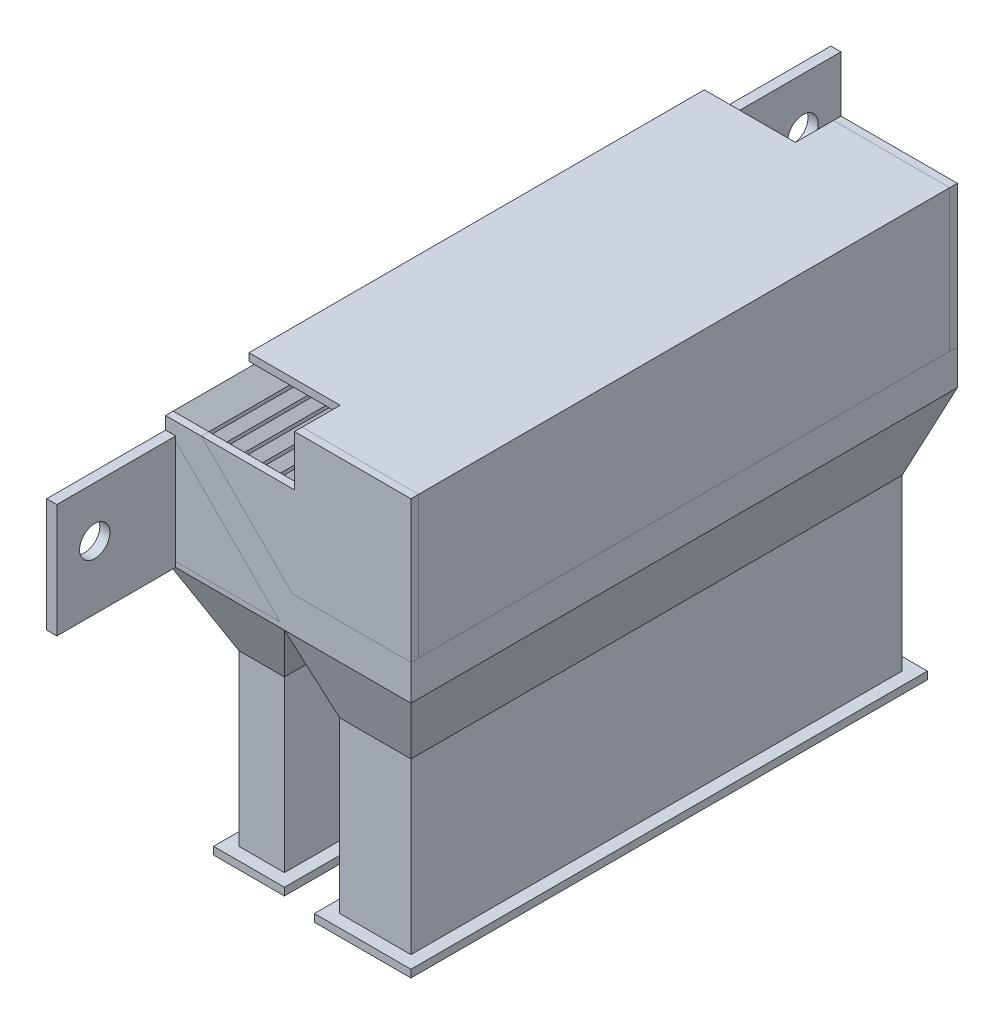
SolidWorks part; units mm, degrees
ref_plane "前视基准面" through (0, 0, 0) normal (0, 0, 1) x (1, 0, 0)
ref_plane "上视基准面" through (0, 0, 0) normal (0, 1, 0) x (1, 0, 0)
ref_plane "右视基准面" through (0, 0, 0) normal (1, 0, 0) x (0, 0, -1)
sketch "草图1" plane through (0, 0, 0) normal (0, 0, 1) x (1, 0, 0)
  line L0 (0, 0) -> (0, 50)
  line L1 (0, 50) -> (50, 0)
  line L3 (0, 0) -> (50, 0)
extrude "拉伸1" add sketch "草图1" along normal blind 216
shell "抽壳1" thickness 2
sketch "草图2" plane through (0, 0, 0) normal (1, 0, 0) x (0, 0, -1)
  line L0 (-216, 25) -> (0, 25) construction
  line L1 (-216, 0) -> (-216, 50) construction
  line L2 (0, 0) -> (0, 50) construction
  line L3 (-108, 50) -> (-108, 0) construction
  line L4 (-216, 50) -> (0, 50) construction
  line L5 (-216, 0) -> (0, 0) construction
  line L7 (-263, 0) -> (47, 0)
  line L8 (-263, 0) -> (-263, 45)
  line L10 (47, 0) -> (47, 45)
  line L15 (-263, 45) -> (47, 45)
  point P12 (-108, 25)
extrude "拉伸3" add sketch "草图2" along normal blind 4
sketch "草图4" plane through (25, 25, 0) normal (0.7071, 0.7071, 0) x (0, 0, -1)
  line L0 (-216, -35.3553) -> (0, -35.3553) construction
  line L1 (-216, 35.3553) -> (-213, 35.3553)
  line L2 (-216, 35.3553) -> (-216, -35.3553)
  line L3 (-216, -35.3553) -> (-213, -35.3553)
  line L4 (-213, 35.3553) -> (-213, -35.3553)
  line L6 (0, 35.3553) -> (-3, 35.3553)
  line L7 (0, 35.3553) -> (0, -35.3553)
  line L8 (0, -35.3553) -> (-3, -35.3553)
  line L9 (-3, 35.3553) -> (-3, -35.3553)
extrude "拉伸4" add sketch "草图4" along normal blind 10
sketch "草图6" plane through (25, 25, 0) normal (0.7071, 0.7071, 0) x (0, 0, -1)
  line L0 (-213, -35.3553) -> (-213, 35.3553) construction
  line L1 (-213, 25.3553) -> (-3, 25.3553)
  line L2 (-213, 25.3553) -> (-213, 24.3553)
  line L3 (-213, 24.3553) -> (-3, 24.3553)
  line L4 (-3, 25.3553) -> (-3, 24.3553)
  line L5 (-3, 35.3553) -> (-3, -35.3553) construction
  line L6 (-213, 35.3553) -> (-3, 35.3553) construction
  line L7 (-3, 20.3553) -> (-3, 19.3553)
  line L8 (-213, 20.3553) -> (-3, 20.3553)
  line L9 (-213, 19.3553) -> (-3, 19.3553)
  line L10 (-213, 20.3553) -> (-213, 19.3553)
  line L11 (-3, 15.3553) -> (-3, 14.3553)
  line L12 (-213, 15.3553) -> (-3, 15.3553)
  line L13 (-213, 14.3553) -> (-3, 14.3553)
  line L14 (-213, 15.3553) -> (-213, 14.3553)
  line L15 (-3, 10.3553) -> (-3, 9.3553)
  line L16 (-213, 10.3553) -> (-3, 10.3553)
  line L17 (-213, 9.3553) -> (-3, 9.3553)
  line L18 (-213, 10.3553) -> (-213, 9.3553)
  line L19 (-3, 5.3553) -> (-3, 4.3553)
  line L20 (-213, 5.3553) -> (-3, 5.3553)
  line L21 (-213, 4.3553) -> (-3, 4.3553)
  line L22 (-213, 5.3553) -> (-213, 4.3553)
  line L23 (-3, 0.3553) -> (-3, -0.6447)
  line L24 (-213, 0.3553) -> (-3, 0.3553)
  line L25 (-213, -0.6447) -> (-3, -0.6447)
  line L26 (-213, 0.3553) -> (-213, -0.6447)
  line L27 (-3, -4.6447) -> (-3, -5.6447)
  line L28 (-213, -4.6447) -> (-3, -4.6447)
  line L29 (-213, -5.6447) -> (-3, -5.6447)
  line L30 (-213, -4.6447) -> (-213, -5.6447)
  line L31 (-3, -9.6447) -> (-3, -10.6447)
  line L32 (-213, -9.6447) -> (-3, -9.6447)
  line L33 (-213, -10.6447) -> (-3, -10.6447)
  line L34 (-213, -9.6447) -> (-213, -10.6447)
  line L35 (-3, -14.6447) -> (-3, -15.6447)
  line L36 (-213, -14.6447) -> (-3, -14.6447)
  line L37 (-213, -15.6447) -> (-3, -15.6447)
  line L38 (-213, -14.6447) -> (-213, -15.6447)
  line L39 (-3, -19.6447) -> (-3, -20.6447)
  line L40 (-213, -19.6447) -> (-3, -19.6447)
  line L41 (-213, -20.6447) -> (-3, -20.6447)
  line L42 (-213, -19.6447) -> (-213, -20.6447)
  line L43 (-3, -24.6447) -> (-3, -25.6447)
  line L44 (-213, -24.6447) -> (-3, -24.6447)
  line L45 (-213, -25.6447) -> (-3, -25.6447)
  line L46 (-213, -24.6447) -> (-213, -25.6447)
  line L47 (-3, -29.6447) -> (-3, -30.6447)
  line L48 (-213, -29.6447) -> (-3, -29.6447)
  line L49 (-213, -30.6447) -> (-3, -30.6447)
  line L50 (-213, -29.6447) -> (-213, -30.6447)
  dimension "D1" = 10
  dimension "D2" = 1
extrude "拉伸5" cut sketch "草图6" against normal blind 3
sketch "草图7" plane through (0, 0, 0) normal (0, -1, 0) x (1, 0, 0)
  line L0 (50, 213) -> (50, 3) construction
  line L3 (44, 213) -> (44, 3)
  line L6 (0, 213) -> (4, 213) construction
  line L7 (44, 213) -> (4, 213)
  line L8 (4, 213) -> (4, 3)
  line L9 (4, 3) -> (44, 3)
  dimension "D1" = 6
extrude "拉伸8" cut sketch "草图7" against normal blind 3
sketch "草图8" plane through (0, 0, 0) normal (0, -1, 0) x (1, 0, 0)
  line L0 (47, 216) -> (47, 0)
  line L5 (1, 0) -> (47, 0)
  line L6 (1, 216) -> (1, 0)
  line L7 (1, 216) -> (47, 216)
extrude "拉伸9" add sketch "草图8" along normal blind 30 draft 25 separate body
sketch "草图9" plane through (0, 0, 0) normal (0, -1, 0) x (1, 0, 0)
  line L4 (47, 216) -> (97, 216)
  line L5 (47, 216) -> (47, 0)
  line L6 (47, 0) -> (97, 0)
  line L7 (97, 216) -> (97, 0)
shell "抽壳2" thickness 3
extrude "拉伸12" add sketch "草图9" along normal blind 30 draft 20 separate body
shell "抽壳3" thickness 3
sketch "草图10" plane through (4, 0, 0) normal (1, 0, 0) x (0, 0, -1)
  line L0 (-263, 0) -> (-216, 0) construction
  line L4 (-263, 45) -> (-263, 0) construction
  line L7 (47, 0) -> (47, 45) construction
  line L8 (0, 0) -> (47, 0) construction
  circle A0 centre (-248, 25) radius 6
  circle A1 centre (32, 25) radius 6
  dimension "D1" = 25
  dimension "D2" = 15
  dimension "D3" = 15
  dimension "D4" = 25
extrude "拉伸13" cut sketch "草图10" against normal blind 30
sketch "草图11" plane through (0, 0, 0) normal (0, 1, 0) x (1, 0, 0)
  line L1 (94, -213) -> (50, -213)
  line L2 (97, 0) -> (50, 0)
  line L3 (97, 0) -> (97, -216)
  line L4 (97, -216) -> (50, -216)
  line L6 (50, -3) -> (50, -213) construction
  line L7 (50, 0) -> (50, -3)
  line L8 (94, -3) -> (50, -3)
  line L9 (94, -3) -> (94, -213)
  line L10 (97, -216) -> (47, -216) construction
  line L11 (50, -213) -> (50, -216)
  line L12 (97, 0) -> (47, 0) construction
  line L18 (47, 0) -> (47, -216) construction
  dimension "D1" = 3
extrude "拉伸15" add sketch "草图11" along normal blind 14
sketch "草图12" plane through (0, 0, -47) normal (0, 0, -1) x (-1, 0, 0)
  line L0 (0, 0) -> (0, 50) construction
  line L1 (0, 0) -> (0, 45) construction
  line L3 (0, 50) -> (-25.0972, 50)
  line L4 (0, 50) -> (0, 57.7185)
  line L5 (0, 57.7185) -> (-25.0972, 57.7185)
  line L6 (-25.0972, 50) -> (-25.0972, 57.7185)
extrude "拉伸16" cut sketch "草图12" against normal blind 300
sketch "草图13" plane through (0, -30, 0) normal (0, -1, 0) x (1, 0, 0)
  line L0 (57.9191, 10.9191) -> (86.0809, 10.9191) construction
  line L1 (57.9191, 205.0809) -> (86.0809, 205.0809)
  line L2 (57.9191, 205.0809) -> (57.9191, 10.9191)
  line L3 (57.9191, 10.9191) -> (86.0809, 10.9191)
  line L4 (86.0809, 205.0809) -> (86.0809, 10.9191)
  line L5 (86.0809, 10.9191) -> (86.0809, 205.0809) construction
  line L6 (60.9191, 202.0809) -> (83.0809, 202.0809)
  line L7 (83.0809, 202.0809) -> (83.0809, 13.9191)
  line L8 (60.9191, 13.9191) -> (83.0809, 13.9191)
  line L9 (60.9191, 202.0809) -> (60.9191, 13.9191)
  dimension "D1" = 3
extrude "拉伸17" add sketch "草图13" along normal blind 70 separate body
sketch "草图14" plane through (0, -30, 0) normal (0, -1, 0) x (1, 0, 0)
  line L0 (17.9892, 199.0108) -> (17.9892, 16.9892)
  line L1 (14.9892, 202.0108) -> (33.0108, 202.0108)
  line L2 (14.9892, 202.0108) -> (14.9892, 13.9892)
  line L3 (14.9892, 13.9892) -> (33.0108, 13.9892)
  line L4 (33.0108, 202.0108) -> (33.0108, 13.9892)
  line L5 (17.9892, 16.9892) -> (30.0108, 16.9892)
  line L6 (30.0108, 199.0108) -> (30.0108, 16.9892)
  line L7 (17.9892, 199.0108) -> (30.0108, 199.0108)
  dimension "D1" = 3
extrude "拉伸18" add sketch "草图14" along normal blind 70 separate body
sketch "草图15" plane through (0, 0, 0) normal (0, 0, -1) x (-1, 0, 0)
  line L0 (-14.1421, 50) -> (0, 50)
  line L1 (-97, 50) -> (-97, 14)
  line L2 (-97, 14) -> (-50.1421, 14)
  line L3 (-50.1421, 14) -> (-14.1421, 50)
  line L4 (-4, 43.1716) -> (-45.1716, 2)
  line L5 (-45.1716, 2) -> (-4, 2)
  line L6 (-4, 2) -> (-4, 43.1716)
  line L7 (0, 50) -> (0, 70)
  line L8 (0, 70) -> (-97, 70)
  line L9 (-97, 70) -> (-97, 50)
extrude "拉伸19" add sketch "草图15" against normal blind 3 separate body
ref_plane "基准面1" through (0, 0, 108) normal (0, 0, 1) x (1, 0, 0)
mirror "镜向2" about plane through (0, 0, 108) normal (0, 0, 1) of bodies 118 119
sketch "草图16" plane through (0, 0, 3) normal (0, 0, 1) x (1, 0, 0)
  line L0 (97, 14) -> (97, 70)
  line L1 (97, 70) -> (0, 70)
  line L2 (0, 70) -> (0, 67)
  line L3 (0, 50) -> (0, 70) construction
  line L4 (97, 14) -> (94, 14)
  line L5 (0, 67) -> (94, 67)
  line L6 (94, 67) -> (94, 14)
extrude "拉伸20" add sketch "草图16" along normal blind 210 separate body
sketch "草图17" plane through (0, 70, 0) normal (0, 1, 0) x (1, 0, 0)
  line L0 (0, 0) -> (97, 0) construction
  line L1 (0, -216) -> (51, -216)
  line L2 (0, -216) -> (0, 0)
  line L3 (0, 0) -> (51, 0)
  line L4 (51, -198) -> (51, -216)
  line L5 (45, -108) -> (0, -108) construction
  line L6 (51, -18) -> (51, 0)
  line L7 (51, -198) -> (15, -198)
  line L9 (51, -18) -> (15, -18)
  line L10 (15, -198) -> (15, -18)
  dimension "D1" = 90
  dimension "D2" = 51
  dimension "D3" = 15
  dimension "D4" = 51
extrude "切除-拉伸1" cut sketch "草图17" against normal blind 20
sketch "草图18" plane through (0, -100, 0) normal (0, -1, 0) x (1, 0, 0)
  line L0 (33.0108, 202.0108) -> (14.9892, 202.0108) construction
  line L1 (57.9191, 205.0809) -> (86.0809, 205.0809)
  line L2 (57.9191, 205.0809) -> (57.9191, 10.9191)
  line L3 (57.9191, 10.9191) -> (86.0809, 10.9191)
  line L4 (86.0809, 205.0809) -> (86.0809, 10.9191)
  line L5 (14.9892, 13.9892) -> (33.0108, 13.9892)
  line L6 (14.9892, 13.9892) -> (14.9892, 202.0108)
  line L7 (14.9892, 202.0108) -> (33.0108, 202.0108)
  line L8 (33.0108, 13.9892) -> (33.0108, 202.0108)
  line L9 (33.0108, 202.0108) -> (14.9892, 202.0108) construction
  line L10 (38.0108, 8.9892) -> (38.0108, 207.0108)
  line L11 (9.9892, 207.0108) -> (38.0108, 207.0108)
  line L12 (9.9892, 8.9892) -> (9.9892, 207.0108)
  line L13 (9.9892, 8.9892) -> (38.0108, 8.9892)
  line L14 (52.9191, 210.0809) -> (91.0809, 210.0809)
  line L15 (91.0809, 210.0809) -> (91.0809, 5.9191)
  line L16 (52.9191, 5.9191) -> (91.0809, 5.9191)
  line L17 (52.9191, 210.0809) -> (52.9191, 5.9191)
  dimension "D1" = 5
  dimension "D2" = 5
extrude "拉伸21" add sketch "草图18" against normal blind 3
